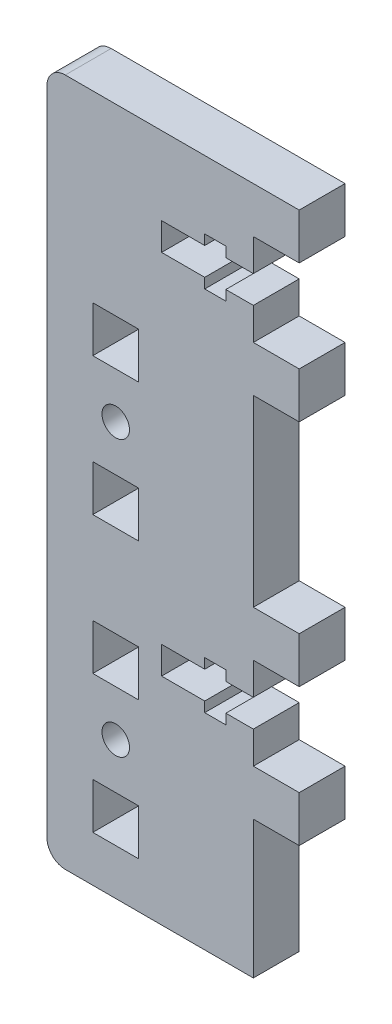
SolidWorks part; units mm, degrees
ref_plane "Front Plane" through (0, 0, 0) normal (0, 0, 1) x (1, 0, 0)
ref_plane "Top Plane" through (0, 0, 0) normal (0, 1, 0) x (1, 0, 0)
ref_plane "Right Plane" through (0, 0, 0) normal (1, 0, 0) x (0, 0, -1)
sketch "Sketch1" plane through (0, 0, 0) normal (0, 0, 1) x (1, 0, 0)
  line L2 (0, 0) -> (0, 126.2811) construction
  line L4 (22.5, 0) -> (22.5, 75) construction
  line L5 (22.5, 55) -> (22.5, 35)
  line L6 (22.5, 15) -> (22.5, 0)
  line L7 (22.5, 75) -> (0, 75)
  line L16 (0, 75) -> (0, 0)
  line L25 (0, 0) -> (22.5, 0)
  point P3 (56, 93.6476)
  point P11 (0, 0)
  point P12 (56, 18.1851)
  point P13 (0, 0)
  point P14 (1.2284, 0)
  line B0 (7.5, 40) -> (7.5, 50) construction
  line B1 (5, 40) -> (5, 35)
  line B2 (5, 40) -> (10, 40)
  line B3 (10, 40) -> (10, 35)
  line B4 (5, 35) -> (10, 35)
  line B5 (5, 50) -> (5, 55)
  line B6 (5, 50) -> (10, 50)
  line B7 (10, 50) -> (10, 55)
  line B8 (5, 55) -> (10, 55)
  line B9 (7.5, 45) -> (0.5276, 45) construction
  circle B10 centre (7.5, 45) radius 1.5
  line B11 (7.5, 10) -> (7.5, 20) construction
  line B12 (5, 10) -> (5, 5)
  line B13 (5, 10) -> (10, 10)
  line B14 (10, 10) -> (10, 5)
  line B15 (5, 5) -> (10, 5)
  line B16 (5, 20) -> (5, 25)
  line B17 (5, 20) -> (10, 20)
  line B18 (10, 20) -> (10, 25)
  line B19 (5, 25) -> (10, 25)
  line B20 (7.5, 15) -> (0.5276, 15) construction
  circle B21 centre (7.5, 15) radius 1.5
  line B22 (19.5, 62.4) -> (17.2, 62.4)
  line B23 (17.2, 66.5) -> (12.5, 66.5)
  line B24 (12.5, 63.5) -> (17.2, 63.5)
  line B25 (17.2, 62.4) -> (17.2, 63.5)
  line B26 (22.5, 65) -> (11.2792, 65) construction
  line B27 (22.5, 63.5) -> (22.5, 60)
  line B28 (27.5, 60) -> (27.5, 55)
  line B29 (27.5, 55) -> (22.5, 55)
  line B30 (27.5, 60) -> (22.5, 60)
  line B31 (22.5, 66.5) -> (22.5, 70)
  line B32 (22.5, 70) -> (27.5, 70)
  line B33 (27.5, 70) -> (27.5, 75)
  line B34 (27.5, 75) -> (22.5, 75)
  line B35 (22.5, 63.5) -> (22.5, 66.5) construction
  line B36 (22.5, 66.5) -> (19.5, 66.5)
  line B37 (17.2, 66.5) -> (17.2, 67.6)
  line B38 (19.5, 67.6) -> (19.5, 66.5)
  line B39 (12.5, 66.5) -> (12.5, 63.5)
  line B40 (19.5, 63.5) -> (19.5, 62.4)
  line B41 (17.2, 67.6) -> (19.5, 67.6)
  line B42 (19.5, 63.5) -> (22.5, 63.5)
  line B43 (12.5, 65) -> (22.5, 65) construction
  line B44 (19.5, 22.4) -> (17.2, 22.4)
  line B45 (17.2, 26.5) -> (12.5, 26.5)
  line B46 (12.5, 23.5) -> (17.2, 23.5)
  line B47 (17.2, 22.4) -> (17.2, 23.5)
  line B48 (22.5, 25) -> (11.2792, 25) construction
  line B49 (22.5, 23.5) -> (22.5, 20)
  line B50 (27.5, 20) -> (27.5, 15)
  line B51 (27.5, 15) -> (22.5, 15)
  line B52 (27.5, 20) -> (22.5, 20)
  line B53 (22.5, 26.5) -> (22.5, 30)
  line B54 (22.5, 30) -> (27.5, 30)
  line B55 (27.5, 30) -> (27.5, 35)
  line B56 (27.5, 35) -> (22.5, 35)
  line B57 (22.5, 23.5) -> (22.5, 26.5) construction
  line B58 (22.5, 26.5) -> (19.5, 26.5)
  line B59 (17.2, 26.5) -> (17.2, 27.6)
  line B60 (19.5, 27.6) -> (19.5, 26.5)
  line B61 (12.5, 26.5) -> (12.5, 23.5)
  line B62 (19.5, 23.5) -> (19.5, 22.4)
  line B63 (17.2, 27.6) -> (19.5, 27.6)
  line B64 (19.5, 23.5) -> (22.5, 23.5)
  line B65 (12.5, 25) -> (22.5, 25) construction
  dimension "D3" = 56
  dimension "D4" = 5
  dimension "D5" = 40
  dimension "D6" = 5
  dimension "D8" = 20
  dimension "D11" = 15
  dimension "D23" = 10
sketch_block_instance "Trou M3 plots 5mm-1"
sketch_block "Trou M3 plots 5mm" parameters "D2"=3, "D1"=5, "D3"=5, "D4"=10
sketch_block_instance "Trou M3 plots 5mm-2"
sketch_block_instance "Insert M3 plots ep 5mm-3"
sketch_block "Insert M3 plots ep 5mm" parameters "D1"=10, "D2"=5, "D3"=5
sketch_block_instance "Decoupe Insert M3-4"
sketch_block "Decoupe Insert M3" parameters "D1"=5.2, "D2"=3, "D3"=2.3, "D4"=3, "D5"=10
sketch_block_instance "Insert M3 plots ep 5mm-4"
extrude "Boss-Extrude1" add sketch "Sketch1" along normal blind 5
fillet "Congé1" radius 2 2 edges at (0, 75, 2.5) (0, 0, 2.5)
